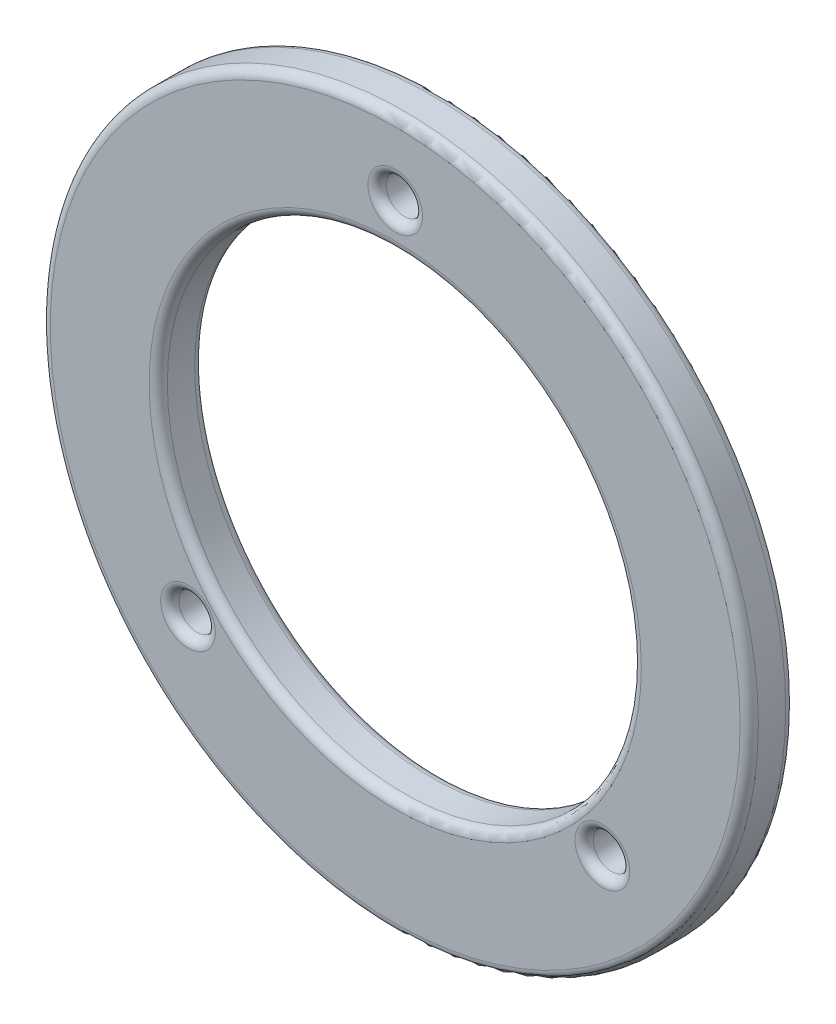
SolidWorks part; units mm, degrees
material "ABS"
ref_plane "Front Plane" through (0, 0, 0) normal (0, 0, 1) x (1, 0, 0)
ref_plane "Top Plane" through (0, 0, 0) normal (0, 1, 0) x (1, 0, 0)
ref_plane "Right Plane" through (0, 0, 0) normal (1, 0, 0) x (0, 0, -1)
sketch "Sketch1" plane through (0, 0, 0) normal (0, 0, 1) x (1, 0, 0)
  line L0 (-28.8671, -25.4559) -> (0, 39.1668) construction
  line L1 (0, 39.1668) -> (28.8671, -25.4559) construction
  circle A0 centre (0, 0) radius 49.3268
  circle A2 centre (0, 39.1668) radius 2.54
  circle A4 centre (0, 0) radius 33.02
  circle A8 centre (28.8671, -25.4559) radius 2.54
  circle A9 centre (-28.8671, -25.4559) radius 2.54
  point P19 (0, 0)
  dimension "D1" = 98.6536
  dimension "D2" = 5.08
  dimension "D7" = 66.04
  dimension "D4" = 70.7771
  dimension "D5" = 57.7342
  dimension "D3" = 10.16
extrude "Boss-Extrude1" add sketch "Sketch1" along normal mid plane 6.35
fillet "Fillet1" radius 1.27 10 edges at (49.3268, 0, -3.175) (2.54, 39.1668, -3.175) (33.02, 0, -3.175) (31.4071, -25.4559, -3.175) (-26.3271, -25.4559, -3.175) (49.3268, 0, 3.175) (2.54, 39.1668, 3.175) (33.02, 0, 3.175) (31.4071, -25.4559, 3.175) (-26.3271, -25.4559, 3.175)
